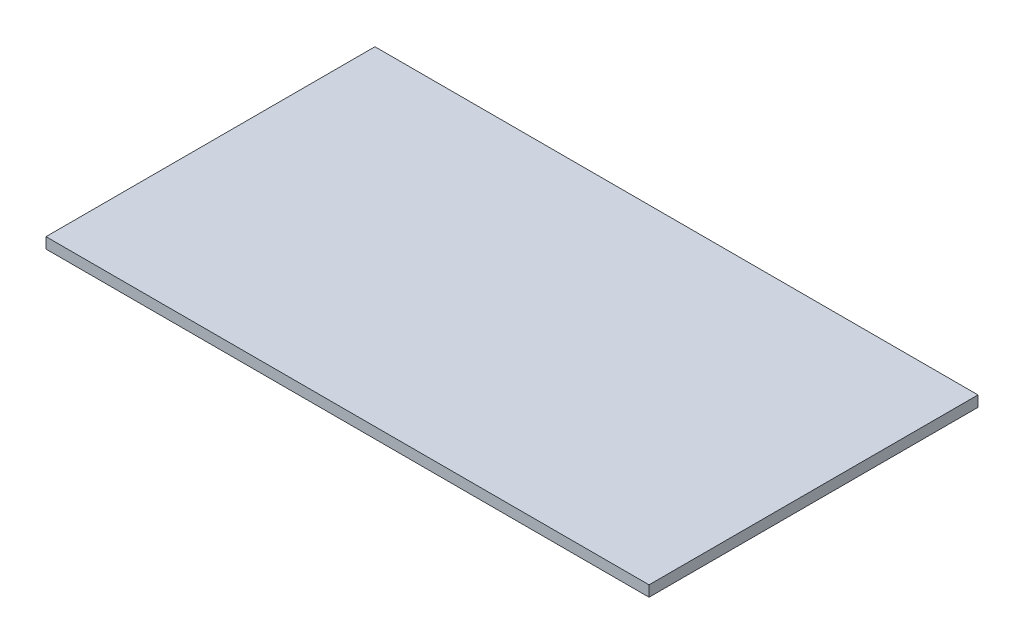
SolidWorks part; units mm, degrees
material "Balsa"
ref_plane "Front Plane" through (0, 0, 0) normal (0, 0, 1) x (1, 0, 0)
ref_plane "Top Plane" through (0, 0, 0) normal (0, 1, 0) x (1, 0, 0)
ref_plane "Right Plane" through (0, 0, 0) normal (1, 0, 0) x (0, 0, -1)
sketch "Sketch1" plane through (0, 0, 0) normal (0, 1, 0) x (1, 0, 0)
  line L1 (-279.4, 152.4) -> (279.4, 152.4)
  line L2 (-279.4, 152.4) -> (-279.4, -152.4)
  line L3 (-279.4, -152.4) -> (279.4, -152.4)
  line L4 (279.4, 152.4) -> (279.4, -152.4)
  line L5 (-279.4, 152.4) -> (279.4, -152.4) construction
  line L6 (-279.4, -152.4) -> (279.4, 152.4) construction
  point P0 (0, 0)
  dimension "D1" = 304.8
  dimension "D2" = 558.8
extrude "Boss-Extrude1" add sketch "Sketch1" along normal blind 10
